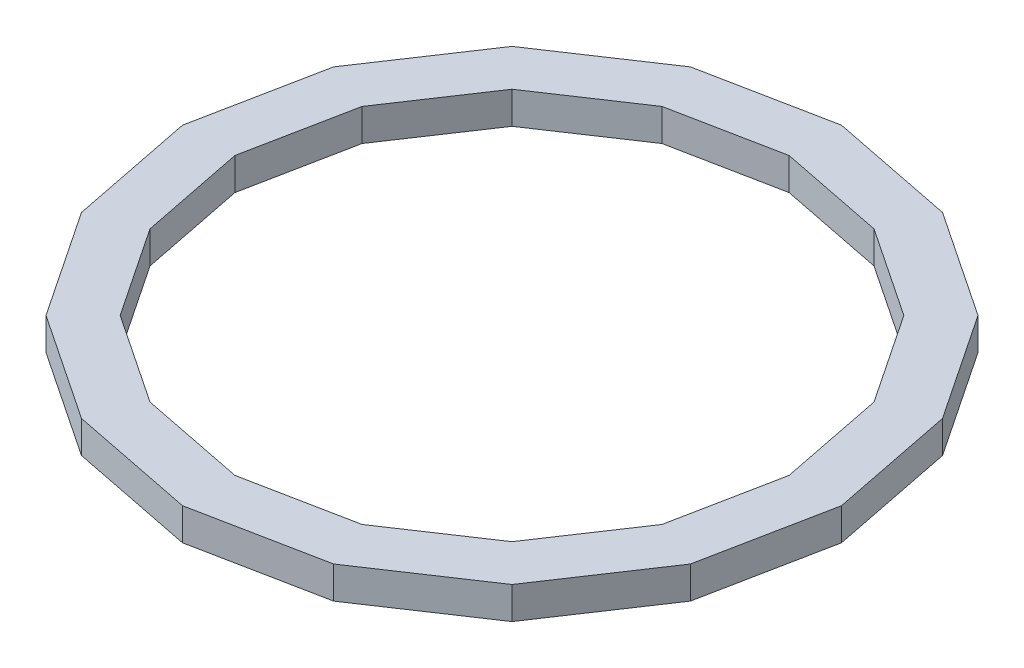
SolidWorks part; units mm, degrees
ref_plane "Front Plane" through (0, 0, 0) normal (0, 0, 1) x (1, 0, 0)
ref_plane "Top Plane" through (0, 0, 0) normal (0, 1, 0) x (1, 0, 0)
ref_plane "Right Plane" through (0, 0, 0) normal (1, 0, 0) x (0, 0, -1)
sketch "Sketch1" plane through (0, 0, 0) normal (0, 1, 0) x (1, 0, 0)
  line L1 (164.217, 0) -> (151.7167, 62.8431)
  line L2 (151.7167, 62.8431) -> (116.119, 116.119)
  line L3 (116.119, 116.119) -> (62.8431, 151.7167)
  line L4 (62.8431, 151.7167) -> (0, 164.217)
  line L5 (0, 164.217) -> (-62.8431, 151.7167)
  line L6 (-62.8431, 151.7167) -> (-116.119, 116.119)
  line L7 (-116.119, 116.119) -> (-151.7167, 62.8431)
  line L8 (-151.7167, 62.8431) -> (-164.217, 0)
  line L9 (-164.217, 0) -> (-151.7167, -62.8431)
  line L10 (-151.7167, -62.8431) -> (-116.119, -116.119)
  line L11 (-116.119, -116.119) -> (-62.8431, -151.7167)
  line L12 (-62.8431, -151.7167) -> (0, -164.217)
  line L13 (0, -164.217) -> (62.8431, -151.7167)
  line L14 (62.8431, -151.7167) -> (116.119, -116.119)
  line L15 (116.119, -116.119) -> (151.7167, -62.8431)
  line L16 (151.7167, -62.8431) -> (164.217, 0)
  line L17 (195.2942, 0) -> (180.4283, 74.7358)
  line L18 (180.4283, 74.7358) -> (138.0938, 138.0938)
  line L19 (138.0938, 138.0938) -> (74.7358, 180.4283)
  line L20 (74.7358, 180.4283) -> (0, 195.2942)
  line L21 (0, 195.2942) -> (-74.7358, 180.4283)
  line L22 (-74.7358, 180.4283) -> (-138.0938, 138.0938)
  line L23 (-138.0938, 138.0938) -> (-180.4283, 74.7358)
  line L24 (-180.4283, 74.7358) -> (-195.2942, 0)
  line L25 (-195.2942, 0) -> (-180.4283, -74.7358)
  line L26 (-180.4283, -74.7358) -> (-138.0938, -138.0938)
  line L27 (-138.0938, -138.0938) -> (-74.7358, -180.4283)
  line L28 (-74.7358, -180.4283) -> (0, -195.2942)
  line L29 (0, -195.2942) -> (74.7358, -180.4283)
  line L30 (74.7358, -180.4283) -> (138.0938, -138.0938)
  line L31 (138.0938, -138.0938) -> (180.4283, -74.7358)
  line L32 (180.4283, -74.7358) -> (195.2942, 0)
  circle A0 centre (0, 0) radius 161.0616 construction
  circle A1 centre (0, 0) radius 191.5416 construction
  dimension "D1" = 76.2
  dimension "D2" = 30.48
extrude "Boss-Extrude1" add sketch "Sketch1" along normal blind 19.05
